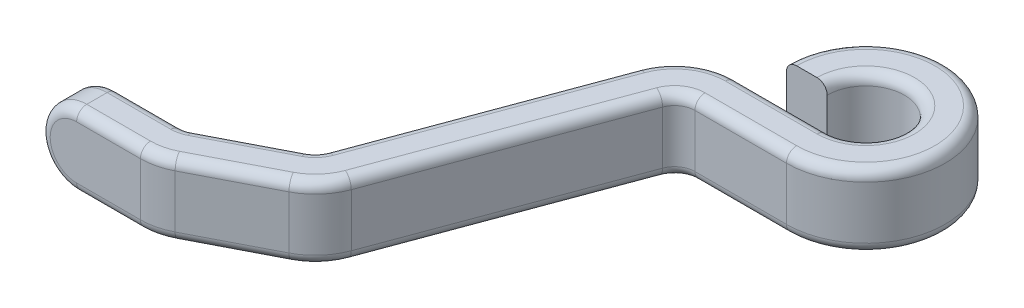
SolidWorks part; units mm, degrees
ref_plane "Front" through (0, 0, 0) normal (0, 0, 1) x (1, 0, 0)
ref_plane "Top" through (0, 0, 0) normal (0, 1, 0) x (1, 0, 0)
ref_plane "Right" through (0, 0, 0) normal (1, 0, 0) x (0, 0, -1)
sketch "Sketch1" plane through (0, 0, 0) normal (0, 0, 1) x (1, 0, 0)
  line L0 (5.3053, 0.9) -> (3.996, 0.9)
  line L1 (5.3053, -0.9) -> (5.3053, 0.9)
  line L2 (3.996, -0.9) -> (5.3053, -0.9)
  line L5 (5.3093, 0.95) -> (3.996, 0.95) construction
  line L6 (5.4053, -1.0222) -> (5.4053, 1.0222) construction
  line L8 (3.996, -0.95) -> (5.3093, -0.95) construction
  arc A0 (3.996, 0.9) -> (3.996, -0.9) centre (3.996, 0) ccw
  arc A2 (3.996, 0.95) -> (3.996, -0.95) centre (3.996, 0) ccw construction
  arc A22 (5.3093, 0.95) -> (5.4053, 1.0222) centre (5.3093, 1.05) ccw construction
  arc A24 (5.4053, -1.0222) -> (5.3093, -0.95) centre (5.3093, -1.05) ccw construction
extrude "Base-Extrude" add sketch "Sketch1" along normal blind 1
sketch "Sketch2" plane through (0, 0, 0) normal (0, 1, 0) x (1, 0, 0)
  line L0 (5.3053, -1) -> (5.3053, 0) construction
  line L1 (5.3053, -1) -> (5.3053, 0) construction
  line L2 (13.6003, 8.7927) -> (7.5184, 8.7927) construction
  line L3 (13.6003, 8.7927) -> (13.6003, 3.4625) construction
  line L4 (13.6003, 7.3427) -> (11.3503, 7.3427)
  line L5 (5.3053, -0.5) -> (5.5625, -0.5)
  line L6 (10.4125, 6.6898) -> (8.3456, 1.1052)
  line L7 (6.0211, -0.3886) -> (7.8664, 0.5637)
  arc A0 (7.8664, 0.5637) -> (8.3456, 1.1052) centre (7.4078, 1.4523) ccw
  circle A2 centre (13.6003, 8.7927) radius 0.95 construction
  arc A3 (13.6003, 7.3427) -> (12.1503, 8.7927) centre (13.6003, 8.7927) ccw
  arc A4 (6.0211, -0.3886) -> (5.5625, -0.5) centre (5.5625, 0.5) cw
  arc A5 (10.4125, 6.6898) -> (11.3503, 7.3427) centre (11.3503, 6.3427) cw
sketch "Sketch3" plane through (5.3053, 0, 0) normal (1, 0, 0) x (0, 0, -1)
  line L4 (0, -0.9) -> (0, 0.9)
  line L5 (0, 0.9) -> (-1, 0.9)
  line L6 (-1, 0.9) -> (-1, -0.9)
  line L7 (-1, -0.9) -> (0, -0.9)
  line L8 (0, -0.9) -> (0, 0.9)
  line L9 (0, 0.9) -> (-1, 0.9)
  line L10 (-1, 0.9) -> (-1, -0.9)
  line L11 (-1, -0.9) -> (0, -0.9)
  dimension "D1" = 0
sweep "Boss-Sweep1" add profiles "Sketch3" path "Sketch2"
fillet "Fillet2" radius 0.25 17 edges at (4.7793, 0.9, 1) (14.9792, -0.9, -10.1715) (12.4753, -0.9, -6.8427) (11.0646, -0.9, -6.753) (9.848, -0.9, -3.7239) (8.5311, -0.9, -0.4582) (7.173, -0.9, 0.3568) (5.9164, -0.9, 0.9576) (5.9164, 0.9, 0.9576) (7.173, 0.9, 0.3568) (8.5311, 0.9, -0.4582) (9.848, 0.9, -3.7239) (11.0646, 0.9, -6.753) (12.4753, 0.9, -6.8427) (14.9792, 0.9, -10.1715) (3.096, 0, 1) (4.7793, -0.9, 1)
fillet "Fillet3" radius 0.25 17 edges at (14.2721, 0.9, -9.4644) (12.4753, 0.9, -7.8427) (10.4933, 0.9, -7.5737) (8.9101, 0.9, -4.071) (7.7822, 0.9, -1.121) (6.7144, 0.9, -0.5318) (5.6805, 0.9, -0.0141) (5.6805, -0.9, -0.0141) (6.7144, -0.9, -0.5318) (7.7822, -0.9, -1.121) (8.9101, -0.9, -4.071) (10.4933, -0.9, -7.5737) (12.4753, -0.9, -7.8427) (14.2721, -0.9, -9.4644) (4.7793, 0.9, 0) (4.7793, -0.9, 0) (3.096, 0, 0)
shell "Shell3" [suppressed] thickness 0.1
